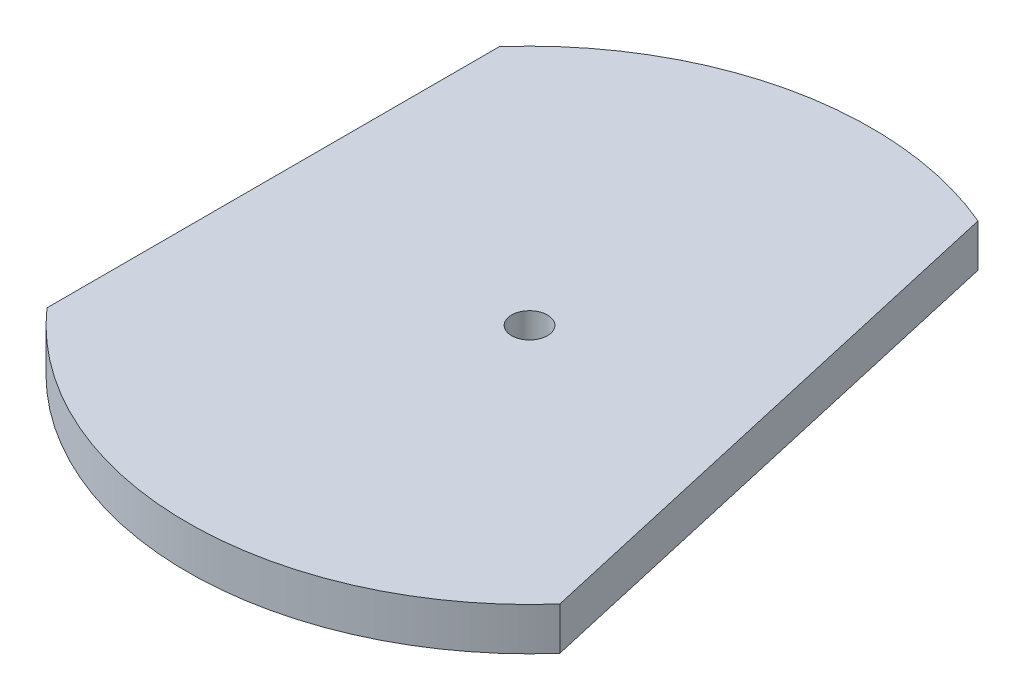
SolidWorks part; units mm, degrees
ref_plane "Front Plane" through (0, 0, 0) normal (0, 0, 1) x (1, 0, 0)
ref_plane "Top Plane" through (0, 0, 0) normal (0, 1, 0) x (1, 0, 0)
ref_plane "Right Plane" through (0, 0, 0) normal (1, 0, 0) x (0, 0, -1)
sketch "Sketch1" plane through (0, 0, 0) normal (0, 1, 0) x (1, 0, 0)
  circle A0 centre (0, 0) radius 2.6667
  circle A1 centre (0, 0) radius 50.8
  dimension "D1" = 101.6
extrude "Boss-Extrude1" add sketch "Sketch1" along normal blind 6.35
sketch "Sketch2" plane through (0, 6.35, 0) normal (0, 1, 0) x (1, 0, 0)
  line L0 (-50.8, 0) -> (-38.1, 0)
  line L1 (-38.1, 0) -> (-38.1, 33.601)
  line L2 (-38.1, 0) -> (-38.1, -33.601)
  line L3 (-38.1, -33.601) -> (-50.8, -33.601)
  line L4 (-50.8, -33.601) -> (-50.8, 33.601)
  line L5 (-50.8, 33.601) -> (-38.1, 33.601)
  line L6 (0, 0) -> (0, 3.3515)
  line L7 (38.1, 0) -> (38.1, 33.601)
  line L8 (50.8, 33.601) -> (38.1, 33.601)
  line L9 (50.8, -33.601) -> (50.8, 33.601)
  line L10 (38.1, -33.601) -> (50.8, -33.601)
  line L11 (38.1, 0) -> (38.1, -33.601)
  circle A0 centre (0, 0) radius 50.8 construction
  point P10 (0, 0)
  circle M8 centre (0, 0) radius 50.8
extrude "Cut-Extrude1" cut sketch "Sketch2" against normal blind 12.7 contours L7 L11 M8 | L0 L1 M8 | L2 L0 M8
sketch "Sketch3" plane through (0, 6.35, 0) normal (0, 1, 0) x (1, 0, 0)
  line L0 (38.1, 33.601) -> (22.86, 33.601)
  line L1 (22.86, 33.601) -> (38.1, -33.601)
  line L2 (38.1, -33.601) -> (16.7159, 60.694)
  line L3 (38.1, -33.601) -> (59.4841, -60.694)
  line L4 (16.7159, 60.694) -> (38.1, 33.601)
  line L5 (59.4841, -60.694) -> (38.1, 33.601)
  line M3 (38.1, -33.601) -> (38.1, 33.601)
  arc M4 (38.1, 33.601) -> (-38.1, 33.601) centre (0, 0) ccw
extrude "Cut-Extrude2" cut sketch "Sketch3" against normal blind 17.348 contours L2 L0 M4 | L0 L1 M3
